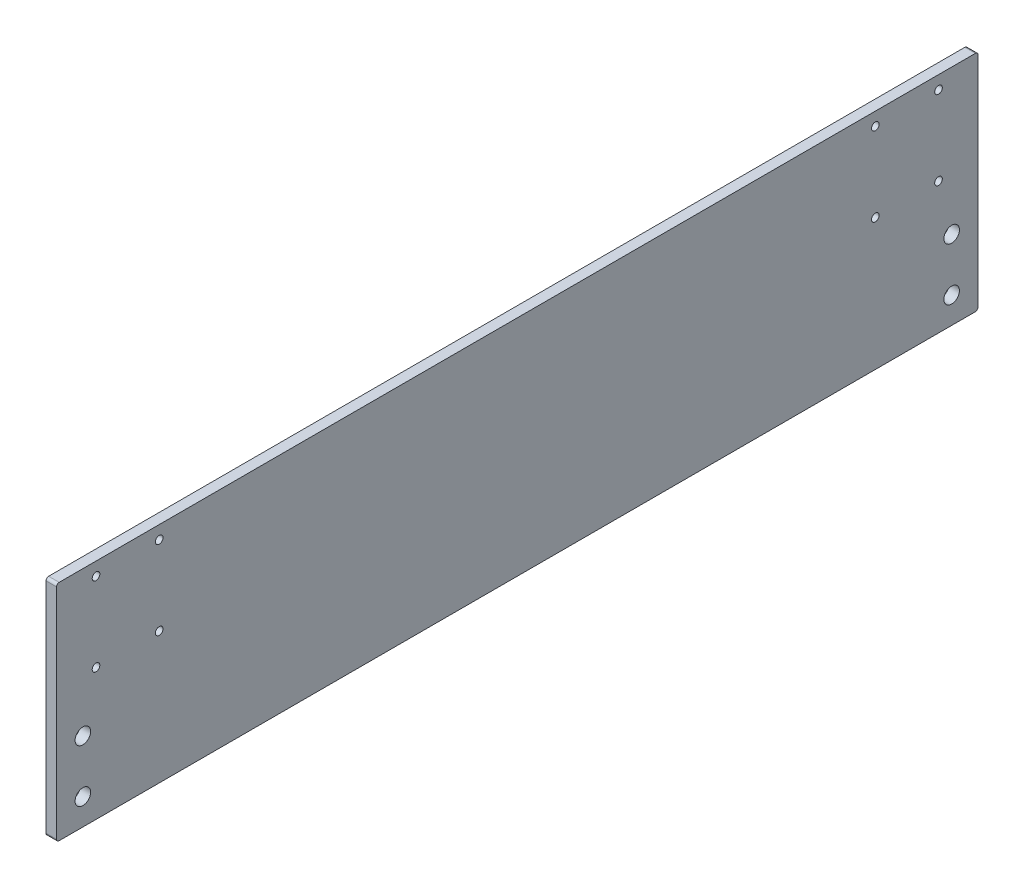
SolidWorks part; units mm, degrees
ref_plane "前视基准面" through (0, 0, 0) normal (0, 0, 1) x (1, 0, 0)
ref_plane "上视基准面" through (0, 0, 0) normal (0, 1, 0) x (1, 0, 0)
ref_plane "右视基准面" through (0, 0, 0) normal (1, 0, 0) x (0, 0, -1)
sketch "草图1" plane through (0, 0, 0) normal (1, 0, 0) x (0, 0, -1)
  line L0 (175, 85) -> (175, 0) construction
  line L1 (0, 0) -> (350, 0)
  line L2 (0, 0) -> (0, 85)
  line L3 (0, 85) -> (350, 85)
  line L4 (350, 0) -> (350, 85)
  circle A0 centre (10, 30) radius 2.95
  circle A1 centre (10, 10) radius 2.95
  circle A2 centre (15, 80) radius 1.45
  circle A3 centre (39, 80) radius 1.45
  circle A4 centre (15, 50) radius 1.45
  circle A5 centre (39, 50) radius 1.45
  circle A6 centre (311, 50) radius 1.45
  circle A7 centre (335, 50) radius 1.45
  circle A8 centre (311, 80) radius 1.45
  circle A9 centre (335, 80) radius 1.45
  circle A10 centre (340, 10) radius 2.95
  circle A11 centre (340, 30) radius 2.95
  dimension "D6" = 5.9
  dimension "D9" = 2.9
  dimension "D1" = 350
  dimension "D2" = 85
  dimension "D3" = 10
  dimension "D4" = 20
  dimension "D5" = 10
  dimension "D7" = 24
  dimension "D8" = 30
  dimension "D10" = 5
  dimension "D11" = 15
extrude "凸台-拉伸1" add sketch "草图1" along normal blind 4
fillet "圆角1" radius 1 4 edges at (2, 0, -350) (2, 85, -350) (2, 0, 0) (2, 85, 0)
